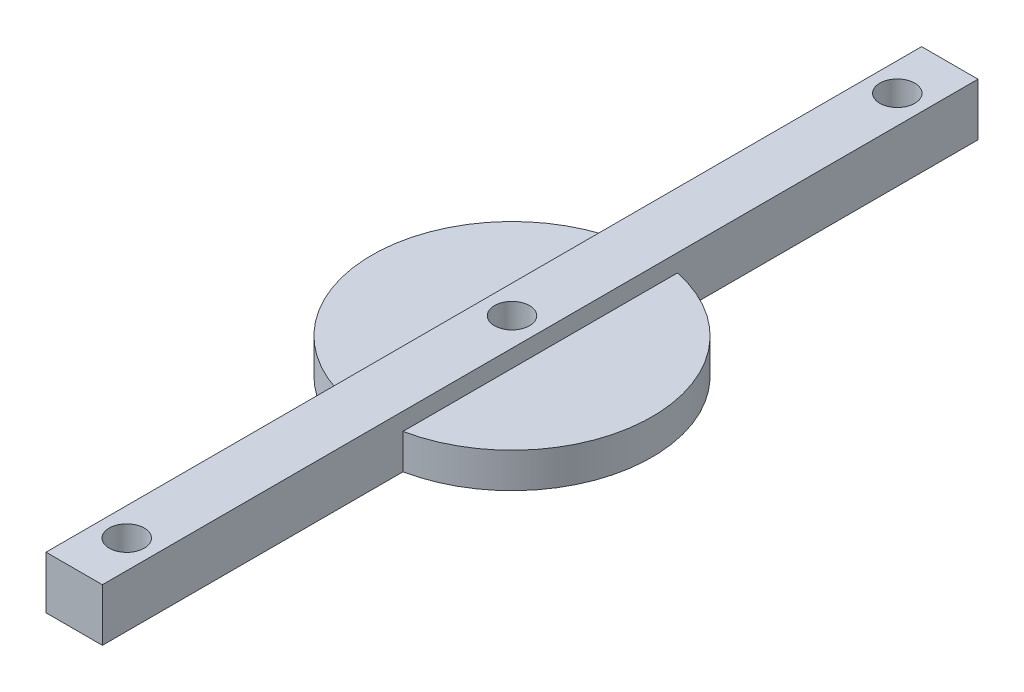
SolidWorks part; units mm, degrees
ref_plane "Alzado" through (0, 0, 0) normal (0, 0, 1) x (1, 0, 0)
ref_plane "Planta" through (0, 0, 0) normal (0, 1, 0) x (1, 0, 0)
ref_plane "Vista lateral" through (0, 0, 0) normal (1, 0, 0) x (0, 0, -1)
sketch "Croquis1" plane through (0, 0, 0) normal (0, 1, 0) x (1, 0, 0)
  line L1 (-8.0496, 125) -> (8.0496, 125)
  line L2 (-8.0496, 125) -> (-8.0496, -125)
  line L3 (-8.0496, -125) -> (8.0496, -125)
  line L4 (8.0496, 125) -> (8.0496, -125)
  line L5 (-8.0496, 125) -> (8.0496, -125) construction
  line L6 (-8.0496, -125) -> (8.0496, 125) construction
  point P0 (0, 0)
  dimension "D1" = 250
extrude "Saliente-Extruir1" add sketch "Croquis1" along normal blind 15
sketch "Croquis2" plane through (0, 0, 0) normal (0, 1, 0) x (1, 0, 0)
  circle A0 centre (0, 0) radius 40
  dimension "D1" = 80
extrude "Saliente-Extruir2" add sketch "Croquis2" along normal blind 10
sketch "Croquis3" plane through (0, 0, 0) normal (0, 1, 0) x (1, 0, 0)
  line L0 (-88.2271, 0) -> (88.2271, 0) construction
  circle A0 centre (0, 0) radius 5
  circle A2 centre (0, 110) radius 5
  circle A3 centre (0, -110) radius 5
  point P9 (0, 0)
  dimension "D1" = 10
  dimension "D2" = 110
extrude "Cortar-Extruir1" cut sketch "Croquis3" along normal through all both and the other way through all
